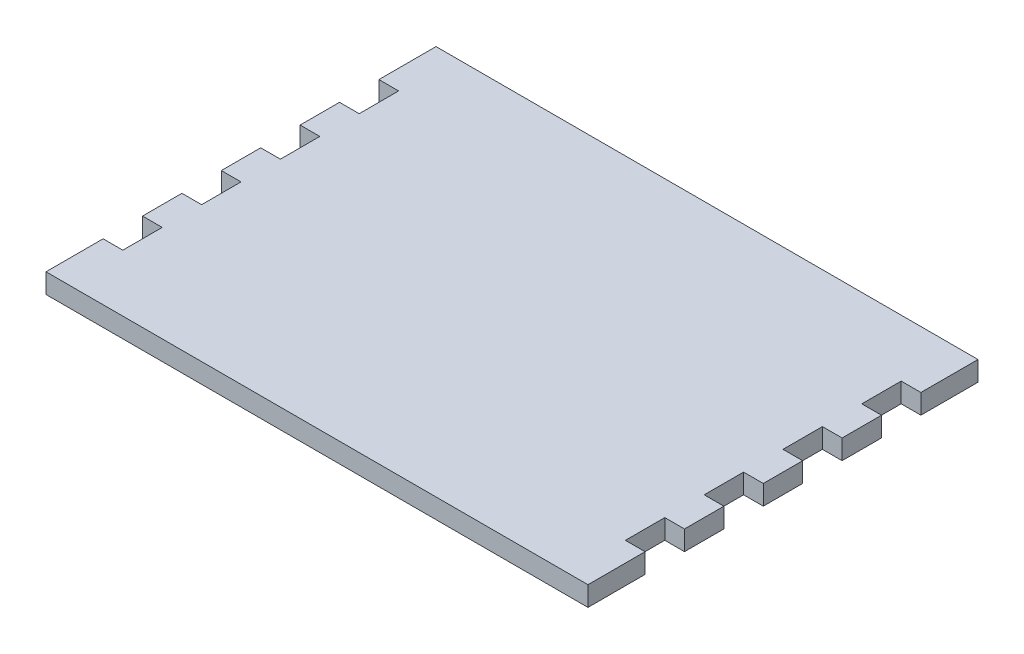
SolidWorks part; units mm, degrees
material "Acrylic (Medium-high impact)"
ref_plane "Front Plane" through (0, 0, 0) normal (0, 0, 1) x (1, 0, 0)
ref_plane "Top Plane" through (0, 0, 0) normal (0, 1, 0) x (1, 0, 0)
ref_plane "Right Plane" through (0, 0, 0) normal (1, 0, 0) x (0, 0, -1)
sketch "Sketch1" plane through (0, 0, 0) normal (0, 1, 0) x (1, 0, 0)
  line L0 (0, 0) -> (0, 9.2059)
  line L1 (0, 9.2059) -> (3.175, 9.2059)
  line L2 (3.175, 9.2059) -> (3.175, 15.5559)
  line L3 (3.175, 15.5559) -> (0, 15.5559)
  line L4 (0, 15.5559) -> (0, 21.9059)
  line L5 (0, 21.9059) -> (3.175, 21.9059)
  line L6 (3.175, 21.9059) -> (3.175, 28.2559)
  line L7 (3.175, 28.2559) -> (0, 28.2559)
  line L8 (0, 28.2559) -> (0, 34.6059)
  line L9 (0, 34.6059) -> (3.175, 34.6059)
  line L10 (3.175, 34.6059) -> (3.175, 40.9559)
  line L11 (3.175, 40.9559) -> (0, 40.9559)
  line L12 (0, 40.9559) -> (0, 47.3059)
  line L13 (0, 47.3059) -> (3.175, 47.3059)
  line L14 (3.175, 47.3059) -> (3.175, 53.6559)
  line L15 (3.175, 53.6559) -> (0, 53.6559)
  line L16 (0, 53.6559) -> (0, 62.8618)
  line L17 (0, 62.8618) -> (3.175, 62.8618)
  line L18 (0, 0) -> (3.175, 0)
  line L19 (3.175, 0) -> (84.175, 0)
  line L20 (43.675, 0) -> (43.675, 62.8618) construction
  line L21 (84.175, 62.8618) -> (3.175, 62.8618)
  line L22 (87.35, 0) -> (84.175, 0)
  line L23 (87.35, 62.8618) -> (84.175, 62.8618)
  line L24 (87.35, 53.6559) -> (87.35, 62.8618)
  line L25 (84.175, 53.6559) -> (87.35, 53.6559)
  line L26 (84.175, 47.3059) -> (84.175, 53.6559)
  line L27 (87.35, 47.3059) -> (84.175, 47.3059)
  line L28 (87.35, 40.9559) -> (87.35, 47.3059)
  line L29 (84.175, 40.9559) -> (87.35, 40.9559)
  line L30 (84.175, 34.6059) -> (84.175, 40.9559)
  line L31 (87.35, 34.6059) -> (84.175, 34.6059)
  line L32 (87.35, 28.2559) -> (87.35, 34.6059)
  line L33 (84.175, 28.2559) -> (87.35, 28.2559)
  line L34 (84.175, 21.9059) -> (84.175, 28.2559)
  line L35 (87.35, 21.9059) -> (84.175, 21.9059)
  line L36 (87.35, 15.5559) -> (87.35, 21.9059)
  line L37 (84.175, 15.5559) -> (87.35, 15.5559)
  line L38 (84.175, 9.2059) -> (84.175, 15.5559)
  line L39 (87.35, 9.2059) -> (84.175, 9.2059)
  line L40 (87.35, 0) -> (87.35, 9.2059)
  dimension "D1" = 9.2059
  dimension "D2" = 6.35
  dimension "D3" = 3.175
  dimension "D4" = 40.5
extrude "Boss-Extrude1" add sketch "Sketch1" along normal blind 3.175
